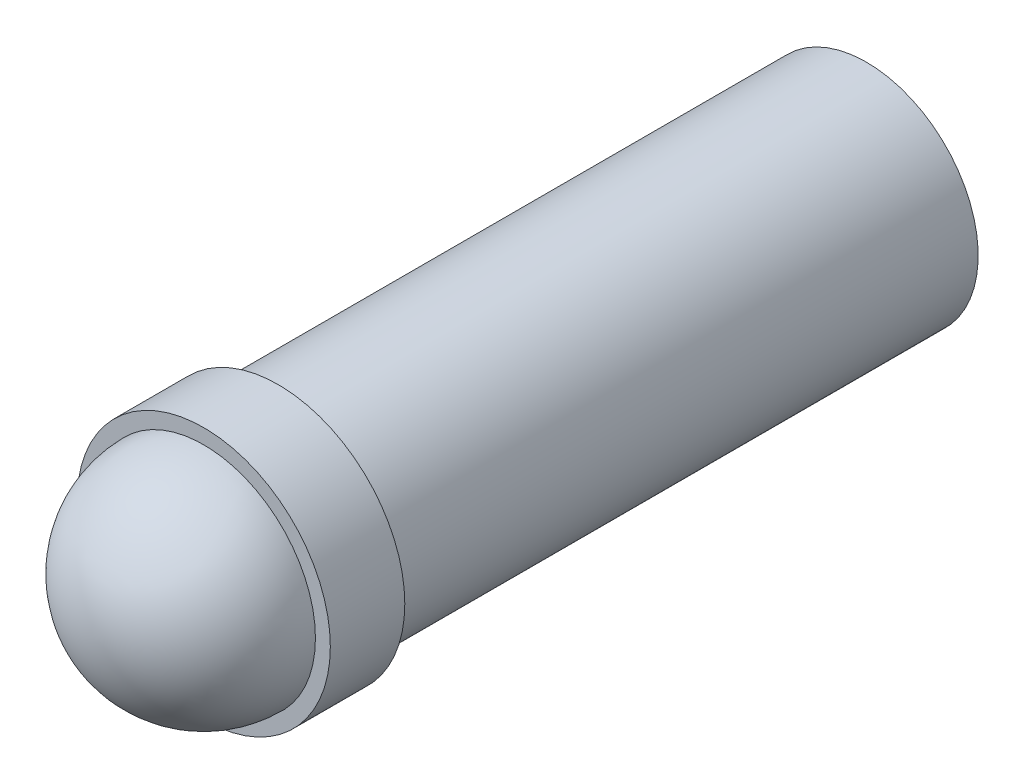
SolidWorks part; units mm, degrees
ref_plane "Front Plane" through (0, 0, 0) normal (0, 0, 1) x (1, 0, 0)
ref_plane "Top Plane" through (0, 0, 0) normal (0, 1, 0) x (1, 0, 0)
ref_plane "Right Plane" through (0, 0, 0) normal (1, 0, 0) x (0, 0, -1)
sketch "Sketch1" plane through (0, 0, 0) normal (0, 0, 1) x (1, 0, 0)
  circle A0 centre (0, 0) radius 15
  dimension "D1" = 30
extrude "Boss-Extrude1" add sketch "Sketch1" along normal blind 104
fillet "Fillet1" radius 15 1 edges at (15, 0, 104)
sketch "Sketch2" plane through (0, 0, 0) normal (0, 0, 1) x (1, 0, 0)
  circle A0 centre (0, 0) radius 17
  circle A1 centre (0, 0) radius 15
  circle A2 centre (0, 0) radius 15
  dimension "D1" = 0
  dimension "D2" = 2
extrude "Boss-Extrude2" add sketch "Sketch2" along normal blind 10 from offset 79
